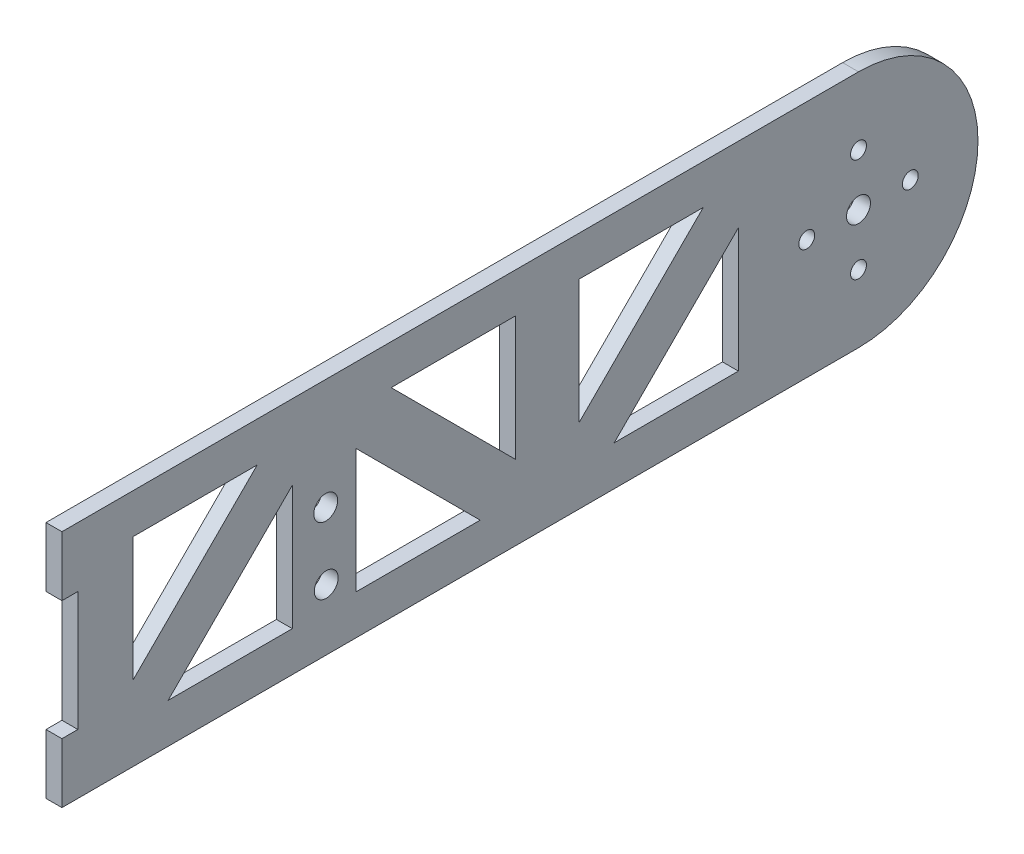
SolidWorks part; units mm, degrees
ref_plane "Front Plane" through (0, 0, 0) normal (0, 0, 1) x (1, 0, 0)
ref_plane "Top Plane" through (0, 0, 0) normal (0, 1, 0) x (1, 0, 0)
ref_plane "Right Plane" through (0, 0, 0) normal (1, 0, 0) x (0, 0, -1)
sketch "Sketch1" plane through (0, 0, 0) normal (1, 0, 0) x (0, 0, -1)
  line L0 (-116.194, 0) -> (-91.0778, 0) construction
  line L1 (0, 15) -> (-100, 15)
  line L2 (-100, -7.5) -> (-100, -15)
  line L3 (0, -15) -> (-68.5513, -15)
  line L4 (-100, 15) -> (-100, 7.5)
  line L5 (-8.2569, 12.5229) -> (-50, 0) construction
  line L6 (-8.2569, -12.5229) -> (-50, 0) construction
  line L7 (-100, 7.5) -> (-98, 7.5)
  line L8 (-67.0778, 18.2684) -> (-67.0778, -29.8477) construction
  line L9 (-100, -7.5) -> (-98, -7.5)
  line L10 (-98, 7.5) -> (-98, -7.5)
  line L11 (-91.0778, 10) -> (-75.4875, 10)
  line L12 (-91.0778, 10) -> (-91.0778, -5.5903)
  line L13 (-86.6682, -10) -> (-73.4392, -10)
  line L14 (-71.0778, 5.5903) -> (-71.0778, -10)
  line L15 (-47.4875, -10) -> (-63.0778, -10)
  line L16 (-86.6682, -10) -> (-71.0778, 5.5903)
  line L17 (-91.0778, -5.5903) -> (-75.4875, 10)
  line L18 (-47.4875, -10) -> (-63.0778, 5.5903)
  line L19 (-63.0778, 5.5903) -> (-63.0778, -10)
  line L20 (-43.0778, -5.5903) -> (-58.6682, 10)
  line L21 (-76.6682, 0) -> (2.0742, 0) construction
  line L22 (-43.0778, 10) -> (-43.0778, -5.5903)
  line L23 (-43.0778, 10) -> (-58.6682, 10)
  line L24 (-39.0778, 19.5906) -> (-39.0778, -28.1382) construction
  line L25 (-35.0778, 10) -> (-35.0778, -5.5903)
  line L26 (-35.0778, 10) -> (-19.4875, 10)
  line L27 (-35.0778, -5.5903) -> (-19.4875, 10)
  line L28 (-15.0778, 5.5903) -> (-15.0778, -10)
  line L29 (-30.6682, -10) -> (-15.0778, 5.5903)
  line L30 (-30.6682, -10) -> (-15.0778, -10)
  line L35 (-71.1797, -10) -> (-71.0778, -10)
  line L36 (-70.8108, -15) -> (-100, -15)
  line L39 (-73.4392, -10) -> (-71.1797, -10)
  line L40 (-70.8108, -15) -> (-68.5513, -15)
  arc A0 (0, -15) -> (0, 15) centre (0, 0) ccw
  circle A1 centre (0, 0) radius 1.5
  point P7 (-50, 0)
  point P15 (-103.6359, 0)
  point P20 (-81.0778, 0)
  dimension "D1" = 30
  dimension "D8" = 3
  dimension "D2" = 30
  dimension "D3" = 100
  dimension "D4" = 15
  dimension "D5" = 2
  dimension "D6" = 8
  dimension "D7" = 8
extrude "Boss-Extrude1" add sketch "Sketch1" along normal blind 2
sketch "Sketch2" plane through (0, 0, 0) normal (-1, 0, 0) x (0, 0, 1)
  line L0 (-7.4003, 0) -> (10.0069, 0) construction
  circle A0 centre (6.5, 0) radius 1
  circle A1 centre (66.8853, 1.0951) radius 1.5
  circle A2 centre (66.8222, -7.3272) radius 1.5
  dimension "D1" = 6.5
  dimension "D2" = 2
extrude "Cut-Extrude1" cut sketch "Sketch2" against normal up to surface (2 mm away) up to face at (2, -4.8032, 20.2746)
pattern_circular "CirPattern1" count 4 over 360 about axis through (0, 0, 0) along (1, 0, 0) of "Cut-Extrude1"
